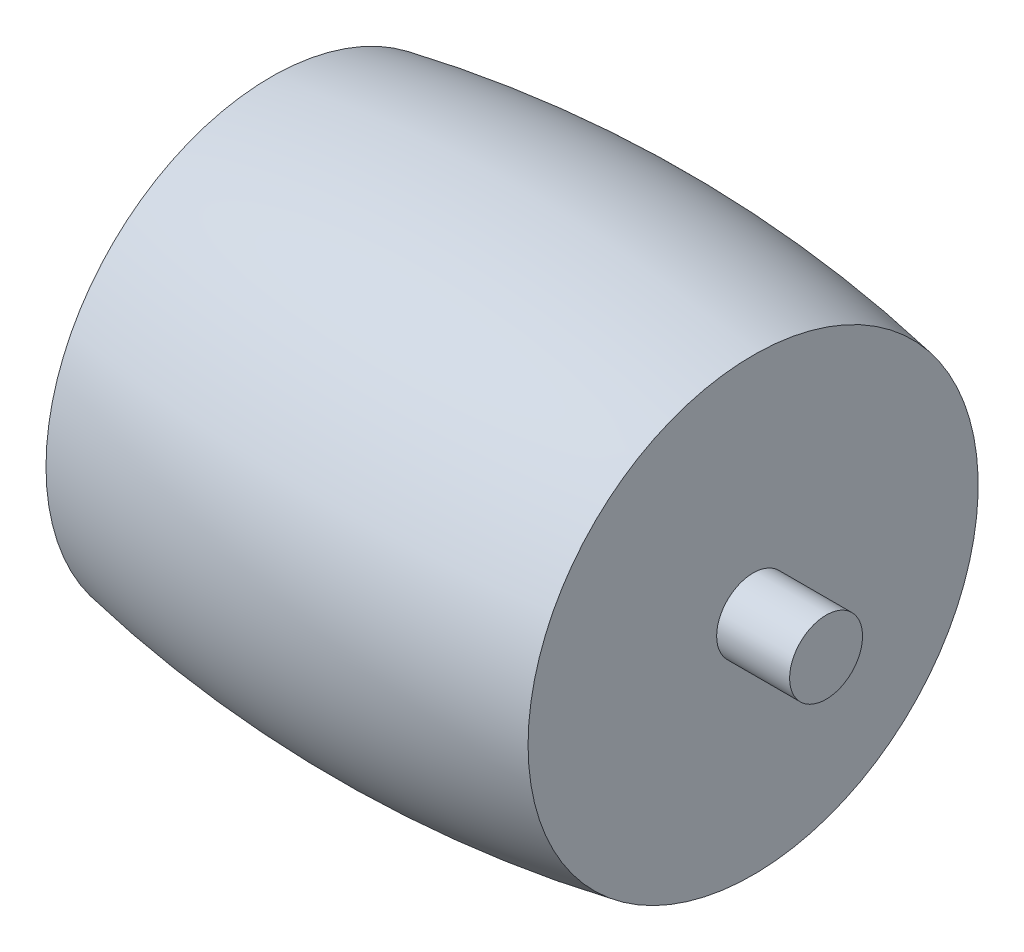
SolidWorks part; units mm, degrees
material "POLYURETHANE (11671)"
ref_plane "Front Plane" through (0, 0, 0) normal (0, 0, 1) x (1, 0, 0)
ref_plane "Top Plane" through (0, 0, 0) normal (0, 1, 0) x (1, 0, 0)
ref_plane "Right Plane" through (0, 0, 0) normal (1, 0, 0) x (0, 0, -1)
sketch "Sketch1" plane through (0, 0, 0) normal (0, 0, 1) x (1, 0, 0)
  line L1 (0, 50) -> (0, 40.5) construction
  line L2 (9.25, 49.1369) -> (9.25, 41.9)
  line L3 (-9.25, 40.5) -> (-12.05, 40.5)
  line L4 (-9.25, 40.5) -> (9.25, 40.5)
  line L7 (-12.05, 41.9) -> (-12.05, 40.5)
  line L8 (9.25, 41.9) -> (12.05, 41.9)
  line L9 (-9.25, 41.9) -> (-12.05, 41.9)
  line L10 (9.25, 40.5) -> (12.05, 40.5)
  line L11 (12.05, 41.9) -> (12.05, 40.5)
  line L12 (-9.25, 49.1369) -> (-9.25, 41.9)
  arc A0 (9.25, 49.1369) -> (-9.25, 49.1369) centre (0, 0) ccw
  dimension "D1" = 100
  dimension "D2" = 18.5
  dimension "D3" = 9.5
  dimension "D4" = 2.8
  dimension "D5" = 1.4
revolve "Revolve1" add sketch "Sketch1" angle 360 about L4
scale "Scale1" bodies to scale 101 scale about centroid uniform scaling yes scale factor 0.24
